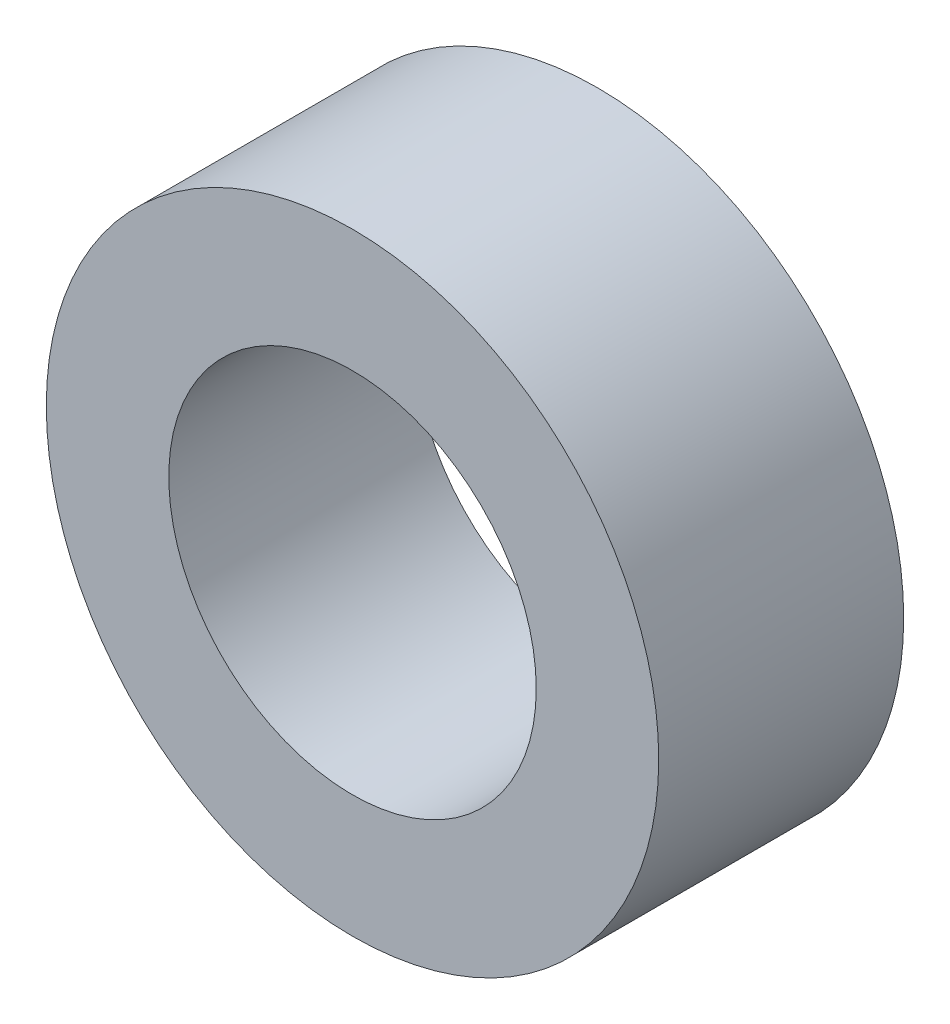
SolidWorks part; units mm, degrees
material "3.0205 (EN-AW 1200)"
ref_plane "Ebene vorne" through (0, 0, 0) normal (0, 0, 1) x (1, 0, 0)
ref_plane "Ebene oben" through (0, 0, 0) normal (0, 1, 0) x (1, 0, 0)
ref_plane "Ebene rechts" through (0, 0, 0) normal (1, 0, 0) x (0, 0, -1)
sketch "Skizze1" plane through (0, 0, 0) normal (0, 0, 1) x (1, 0, 0)
  circle A0 centre (-1.2222, 0.8195) radius 1.5
  circle A1 centre (-1.2222, 0.8195) radius 2.5
  dimension "D1" = 5
  dimension "D2" = 3
extrude "Aufsatz-Linear austragen1" add sketch "Skizze1" along normal blind 2
